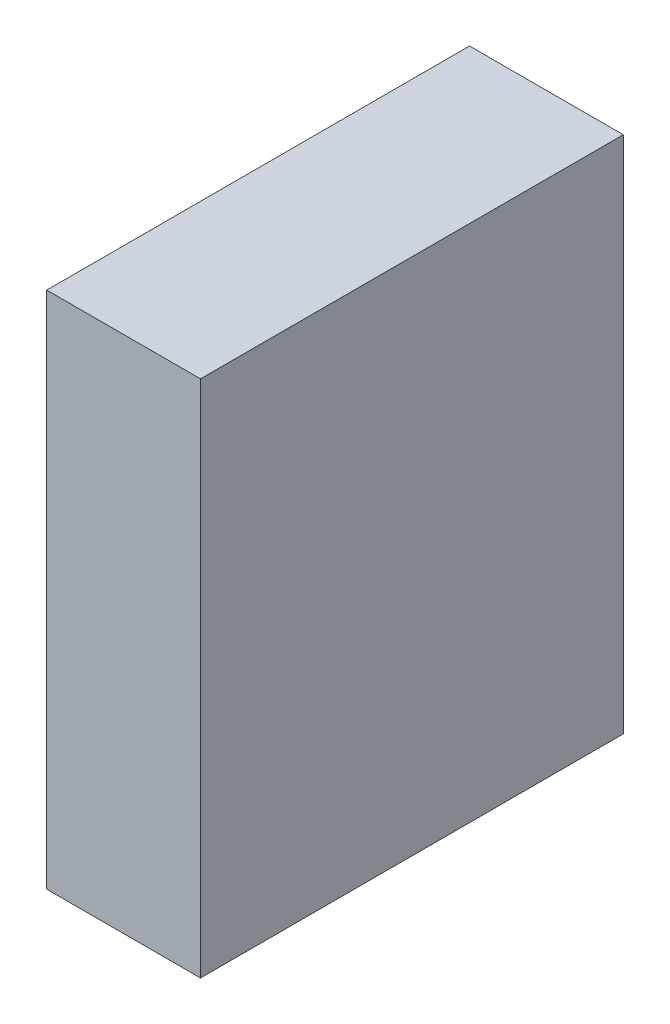
SolidWorks part; units mm, degrees
ref_plane "Front Plane" through (0, 0, 0) normal (0, 0, 1) x (1, 0, 0)
ref_plane "Top Plane" through (0, 0, 0) normal (0, 1, 0) x (1, 0, 0)
ref_plane "Right Plane" through (0, 0, 0) normal (1, 0, 0) x (0, 0, -1)
sketch "Sketch1" plane through (0, 0, 0) normal (0, 1, 0) x (1, 0, 0)
  line L1 (-6.6667, 18.3333) -> (6.6667, 18.3333)
  line L2 (-6.6667, 18.3333) -> (-6.6667, -18.3333)
  line L3 (-6.6667, -18.3333) -> (6.6667, -18.3333)
  line L4 (6.6667, 18.3333) -> (6.6667, -18.3333)
  line L5 (-6.6667, 18.3333) -> (6.6667, -18.3333) construction
  line L6 (-6.6667, -18.3333) -> (6.6667, 18.3333) construction
  point P0 (0, 0)
  dimension "D1" = 13.3333
  dimension "D2" = 36.6667
extrude "Boss-Extrude1" add sketch "Sketch1" along normal blind 45 contours L4 L3 L2 L1
